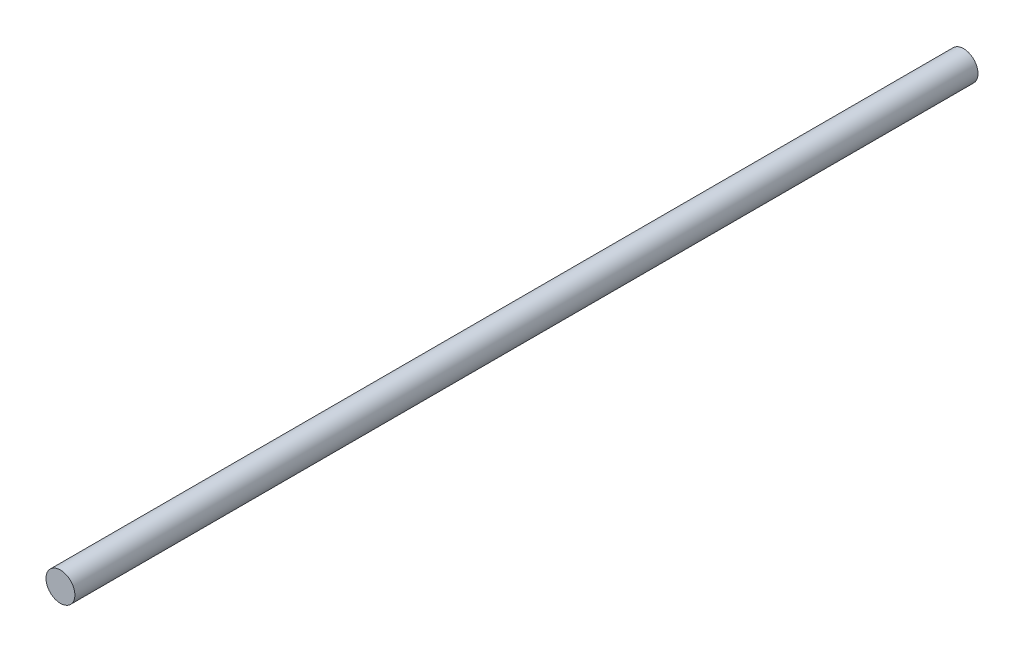
SolidWorks part; units mm, degrees
ref_plane "前视基准面" through (0, 0, 0) normal (0, 0, 1) x (1, 0, 0)
ref_plane "上视基准面" through (0, 0, 0) normal (0, 1, 0) x (1, 0, 0)
ref_plane "右视基准面" through (0, 0, 0) normal (1, 0, 0) x (0, 0, -1)
sketch "草图1" plane through (0, 0, 0) normal (0, 0, 1) x (1, 0, 0)
  circle A0 centre (0, 0) radius 4
  dimension "D1" = 8
extrude "凸台-拉伸1" add sketch "草图1" along normal blind 250
